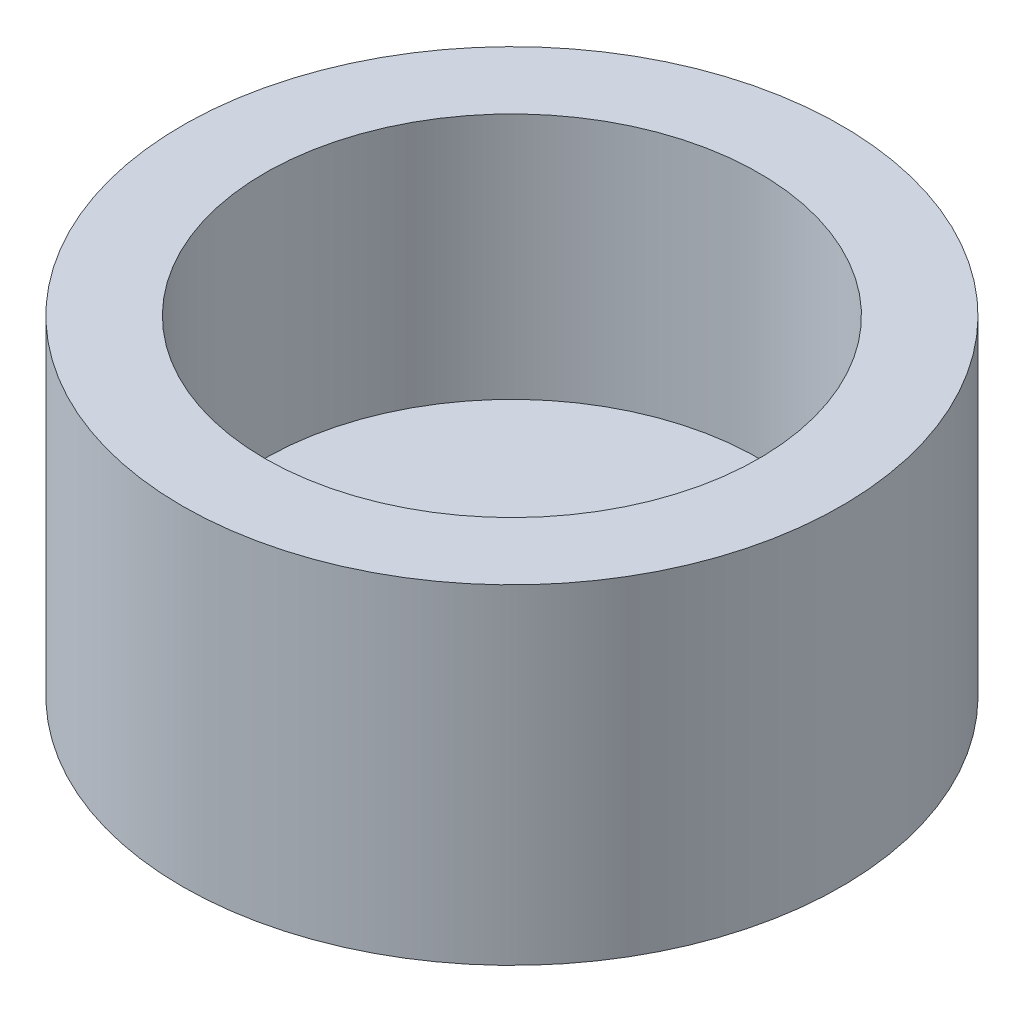
SolidWorks part; units mm, degrees
ref_plane "Front" through (0, 0, 0) normal (0, 0, 1) x (1, 0, 0)
ref_plane "Top" through (0, 0, 0) normal (0, 1, 0) x (1, 0, 0)
ref_plane "Right" through (0, 0, 0) normal (1, 0, 0) x (0, 0, -1)
sketch "Sketch1" plane through (0, 0, 0) normal (0, 0, 1) x (1, 0, 0)
  line L0 (0, 0) -> (25.4, 0)
  line L1 (50, 0) -> (-50, 0) construction
  line L2 (25.4, 0) -> (25.4, 25.4)
  line L3 (25.4, 25.4) -> (19.05, 25.4)
  line L4 (19.05, 25.4) -> (19.05, 6.35)
  line L5 (19.05, 6.35) -> (0, 6.35)
  line L6 (0, -50) -> (0, 50) construction
  line L7 (0, 6.35) -> (0, 0)
  dimension "D1" = 19.05
  dimension "D2" = 6.35
  dimension "D3" = 25.4
revolve "Revolve1" add sketch "Sketch1" angle 360 about L7
sketch "Sketch2" plane through (0, 6.35, 0) normal (0, 1, 0) x (1, 0, 0)
  point P0 (0, 0)
hole_wizard "1/4 Clearance Hole1" positions "Sketch4" profile "Sketch3" hole size "1/4" standard "ANSI Inch" end condition through all
sketch "Sketch4" plane through (0, 6.35, 0) normal (0, 1, 0) x (1, 0, 0)
  point P0 (0, 0)
sketch "Sketch3" plane through (0, 6.35, 0) normal (1, 0, 0) x (0, 0, 1)
  line L0 (0, 0) -> (0, 6.35)
  line L1 (0, 6.35) -> (3.3782, 6.35)
  line L2 (3.3782, 6.35) -> (3.3782, 0)
  line L5 (3.3782, 0) -> (0, 0)
  line L11 (0, -6.35) -> (0, 107.95) construction
  dimension "Thru Hole Dia." = 6.7564
  dimension "Thru Hole Depth" = 6.35
